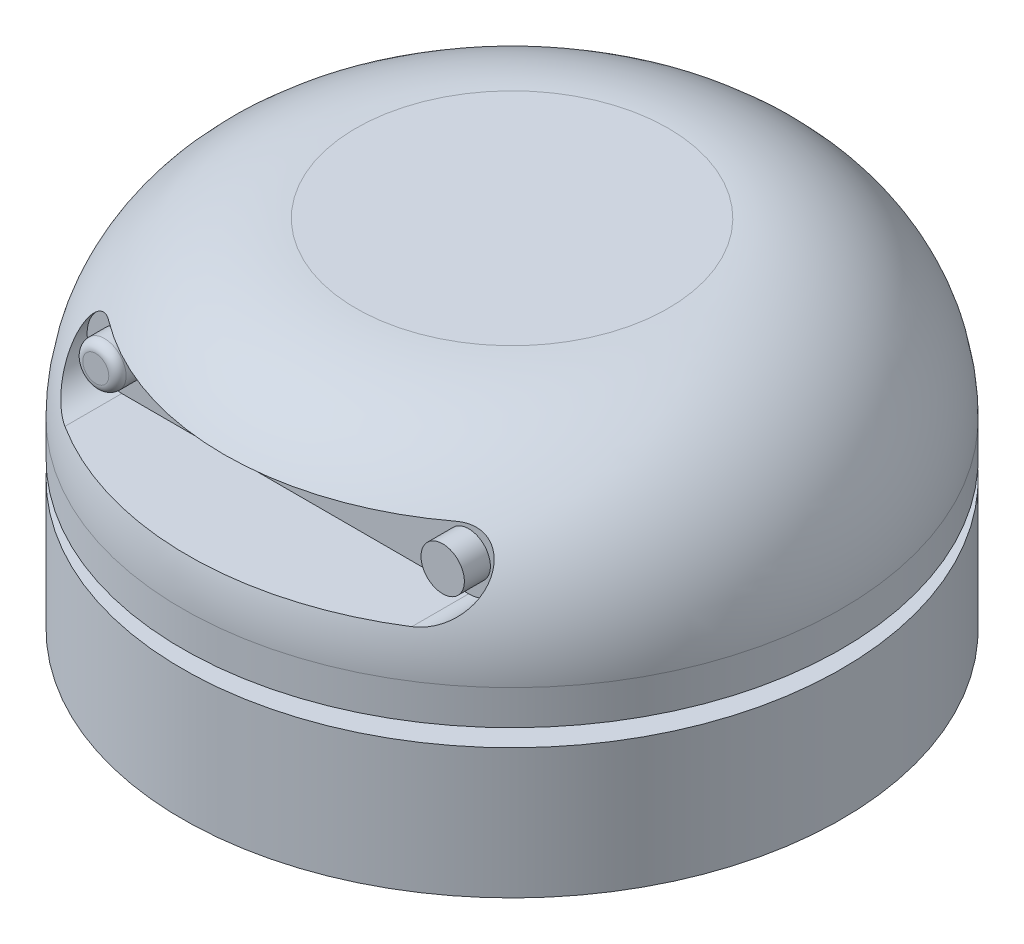
SolidWorks part; units mm, degrees
ref_plane "前视基准面" through (0, 0, 0) normal (0, 0, 1) x (1, 0, 0)
ref_plane "上视基准面" through (0, 0, 0) normal (0, 1, 0) x (1, 0, 0)
ref_plane "右视基准面" through (0, 0, 0) normal (1, 0, 0) x (0, 0, -1)
sketch "草图1" plane through (0, 0, 0) normal (0, 0, 1) x (1, 0, 0)
  line L0 (0, 0) -> (0, 54.3327) construction
  line L1 (0, 0) -> (38, 0)
  line L2 (38, 0) -> (38, 15)
  line L3 (38, 15) -> (35, 15)
  line L4 (35, 15) -> (35, 17)
  line L5 (35, 17) -> (38, 17)
  line L6 (38, 17) -> (38, 21)
  line L7 (18, 41) -> (0, 41)
  line L8 (0, 41) -> (0, 0)
  arc A0 (38, 21) -> (18, 41) centre (18, 21) ccw
  dimension "D6" = 20
  dimension "D1" = 76
  dimension "D2" = 15
  dimension "D3" = 41
  dimension "D4" = 2
  dimension "D5" = 70
revolve "旋转1" add sketch "草图1" angle 360 about L0
sketch "草图2" plane through (0, 0, 0) normal (0, 0, 1) x (1, 0, 0)
  line L0 (-20, 30) -> (20, 30) construction
  line L1 (-20, 34) -> (20, 34)
  line L2 (-20, 26) -> (20, 26)
  arc A0 (-20, 34) -> (-20, 26) centre (-20, 30) ccw
  arc A1 (20, 26) -> (20, 34) centre (20, 30) ccw
  point P2 (0, 30)
  dimension "D1" = 4
  dimension "D2" = 40
  dimension "D3" = 30
extrude "切除-拉伸1" cut sketch "草图2" against normal blind 15 from offset 40
sketch "草图3" plane through (0, 0, 25) normal (0, 0, 1) x (1, 0, 0)
  circle A0 centre (-20, 30) radius 2.5
  circle A1 centre (20, 30) radius 2.5
  dimension "D1" = 5
extrude "凸台-拉伸1" add sketch "草图3" along normal blind 3
fillet "圆角1" radius 1 1 edges at (-17.5, 30, 28)
